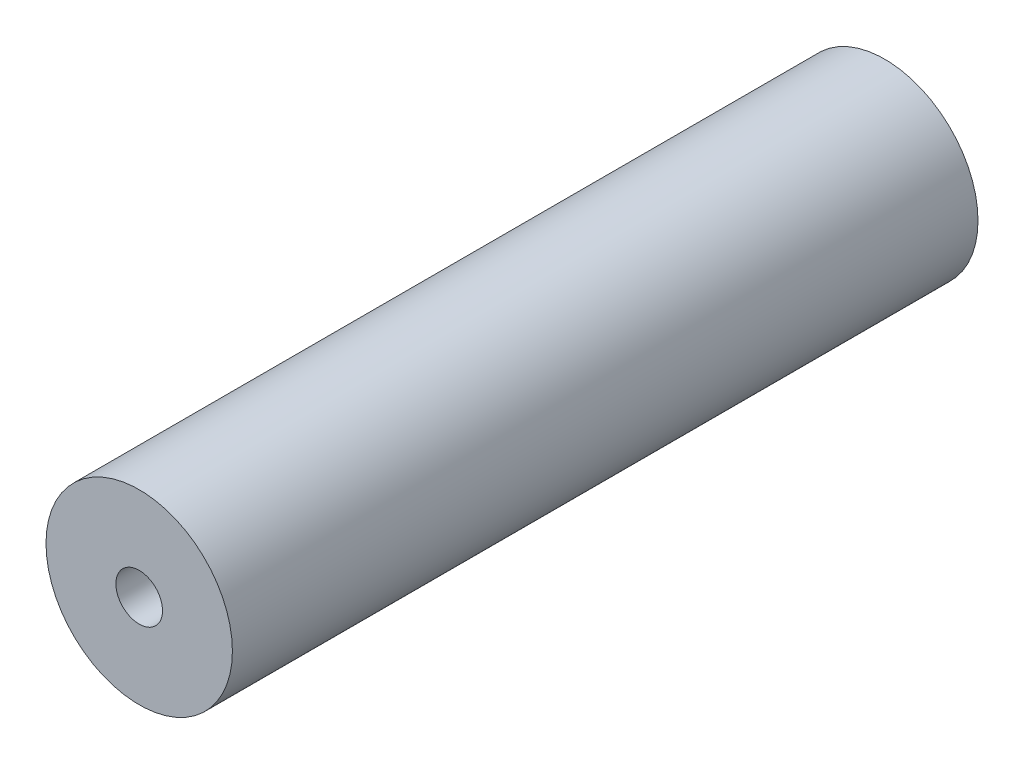
SolidWorks part; units mm, degrees
ref_plane "Front Plane" through (0, 0, 0) normal (0, 0, 1) x (1, 0, 0)
ref_plane "Top Plane" through (0, 0, 0) normal (0, 1, 0) x (1, 0, 0)
ref_plane "Right Plane" through (0, 0, 0) normal (1, 0, 0) x (0, 0, -1)
sketch "Sketch1" plane through (0, 0, 0) normal (0, 0, 1) x (1, 0, 0)
  circle A0 centre (0, 0) radius 25.4
  dimension "D1" = 50.8
extrude "Boss-Extrude1" add sketch "Sketch1" along normal blind 203.2
sketch "Sketch2" plane through (0, 0, 203.2) normal (0, 0, 1) x (1, 0, 0)
  circle A0 centre (0, 0) radius 6.35
  dimension "D1" = 12.7
extrude "Cut-Extrude1" cut sketch "Sketch2" against normal through all
